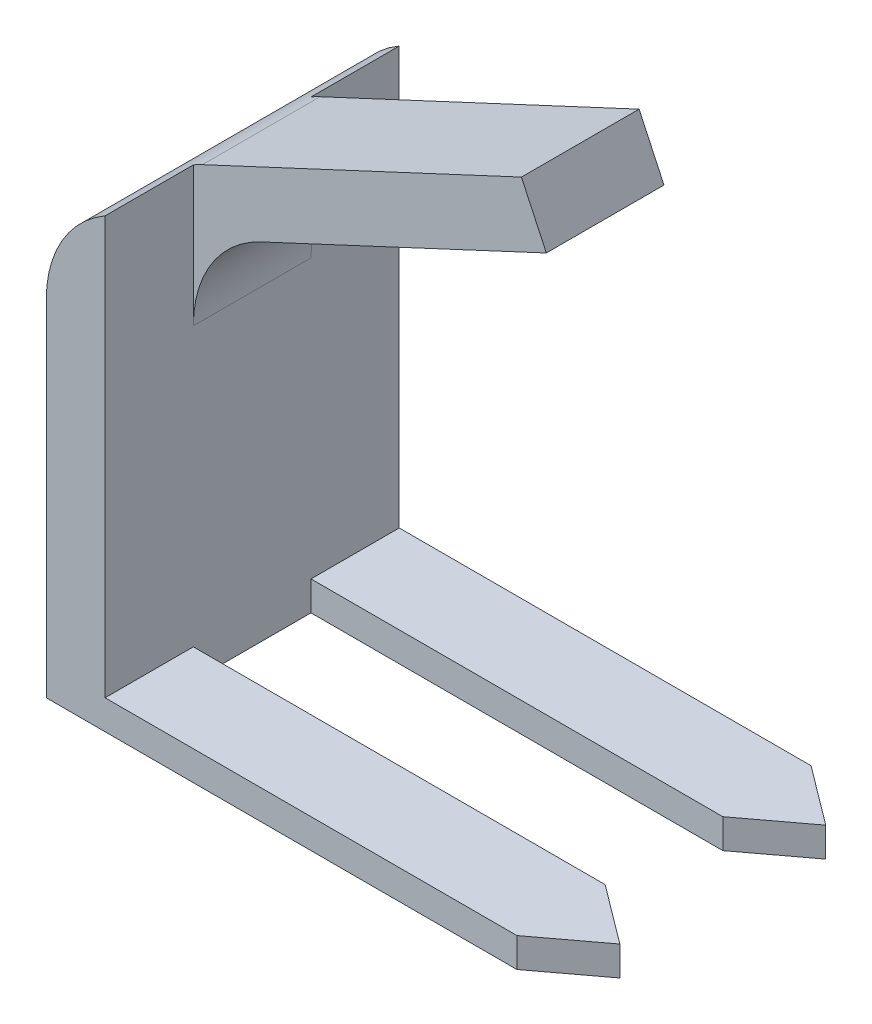
SolidWorks part; units mm, degrees
ref_plane "Alzado" through (0, 0, 0) normal (0, 0, 1) x (1, 0, 0)
ref_plane "Planta" through (0, 0, 0) normal (0, 1, 0) x (1, 0, 0)
ref_plane "Vista lateral" through (0, 0, 0) normal (1, 0, 0) x (0, 0, -1)
sketch "Croquis1" plane through (0, 0, 0) normal (0, 0, 1) x (1, 0, 0)
  line L0 (0, 5) -> (0, 0)
  line L1 (0, 0) -> (-90, 0)
  line L2 (-90, 0) -> (-90, 71.3707)
  line L3 (-80, 5) -> (-20, 5) construction
  line L4 (-80, 65) -> (-80, 5)
  line L5 (-80, 5) -> (0, 5)
  line L6 (-80, 65) -> (-20, 92.9785)
  line L7 (-20, 92.9785) -> (-24.2262, 102.0415)
  line L8 (-24.2262, 102.0415) -> (-90, 71.3707)
  line L9 (-20, 5) -> (-20, 117.6805) construction
  dimension "D1" = 5
  dimension "D2" = 80
  dimension "D3" = 10
  dimension "D4" = 10
  dimension "D5" = 60
  dimension "D6" = 20
  dimension "D7" = 25
extrude "Saliente-Extruir1" add sketch "Croquis1" along normal mid plane 50
fillet "Redondeo1" radius 20 2 edges at (-80, 65, 0) (-90, 71.3707, 0)
sketch "Croquis2" plane through (0, 5, 0) normal (0, 1, 0) x (1, 0, 0)
  line L0 (-80, -10) -> (-80, -25)
  line L1 (-80, 25) -> (-10, 25)
  line L2 (-80, -25) -> (-10, -25)
  line L3 (-10, -10) -> (-80, -10)
  line L4 (-10, 10) -> (-80, 10)
  line L5 (-80, 10) -> (-80, 25)
  line L6 (0, -25) -> (0, 25) construction
  line L7 (0, 25) -> (0, 17.5)
  line L8 (-10, -25) -> (0, -17.5)
  line L9 (-10, -10) -> (0, -17.5)
  line L10 (-10, 10) -> (0, 17.5)
  line L11 (-10, 25) -> (0, 17.5)
  line M1 (0, 25) -> (-80, 25)
  line M2 (-80, 25) -> (-80, -25)
  line M3 (-80, -25) -> (0, -25)
  line M4 (0, -25) -> (0, 25)
  dimension "D1" = 10
  dimension "D2" = 10
  dimension "D3" = 7.5
  dimension "D4" = 7.5
  dimension "D5" = 70
  dimension "D6" = 70
extrude "Cortar-Extruir1" cut sketch "Croquis2" against normal blind 10 contours L10 L4 L3 L9 M2 M4 | L11 M1 M4 | L8 M3 M4
sketch "Croquis3" plane through (0, 5, 0) normal (0, 1, 0) x (1, 0, 0)
  line L1 (-80, -10) -> (-10, -10)
  line L2 (-80, -10) -> (-80, -25)
  line L3 (-80, -25) -> (-10, -25)
  line L4 (-10, -10) -> (-10, -25)
  line L5 (-80, 10) -> (-10, 10)
  line L6 (-80, 10) -> (-80, 25)
  line L7 (-80, 25) -> (-10, 25)
  line L8 (-10, 10) -> (-10, 25)
extrude "Cortar-Extruir2" cut sketch "Croquis3" along normal through all
